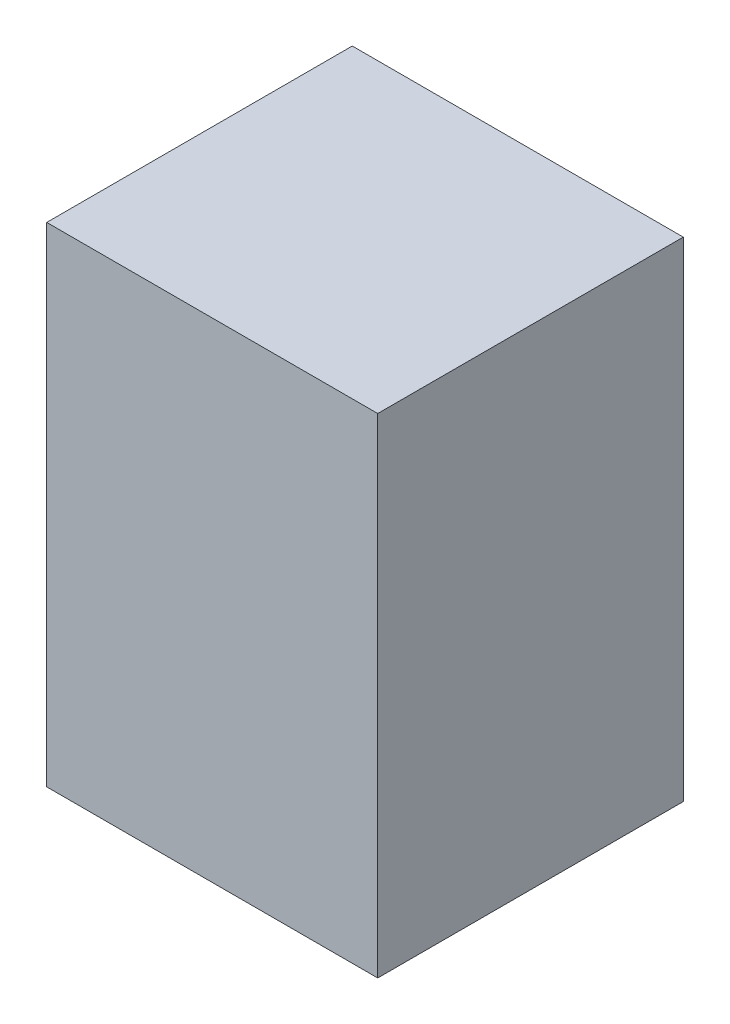
SolidWorks part; units mm, degrees
ref_plane "Front Plane" through (0, 0, 0) normal (0, 0, 1) x (1, 0, 0)
ref_plane "Top Plane" through (0, 0, 0) normal (0, 1, 0) x (1, 0, 0)
ref_plane "Right Plane" through (0, 0, 0) normal (1, 0, 0) x (0, 0, -1)
sketch "Sketch1" plane through (0, 0, 0) normal (0, 1, 0) x (1, 0, 0)
  line L1 (0, 0) -> (1651, 0)
  line L2 (0, 0) -> (0, 1524)
  line L3 (0, 1524) -> (1651, 1524)
  line L4 (1651, 0) -> (1651, 1524)
  dimension "D1" = 1651
  dimension "D2" = 1524
extrude "Boss-Extrude1" add sketch "Sketch1" along normal blind 2438.4
